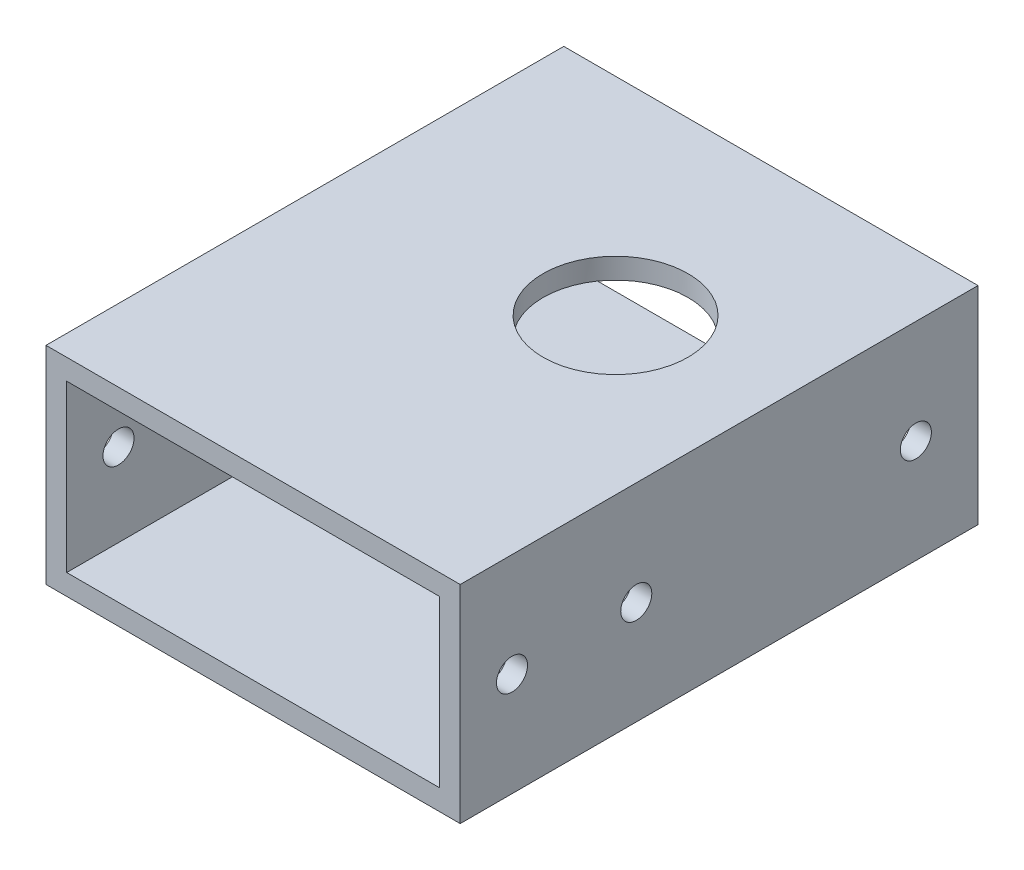
SolidWorks part; units mm, degrees
ref_plane "前视基准面" through (0, 0, 0) normal (0, 0, 1) x (1, 0, 0)
ref_plane "上视基准面" through (0, 0, 0) normal (0, 1, 0) x (1, 0, 0)
ref_plane "右视基准面" through (0, 0, 0) normal (1, 0, 0) x (0, 0, -1)
other "Configuration Table"
sketch "草图1" plane through (0, 0, 0) normal (0, 0, 1) x (1, 0, 0)
  line L1 (-20, 10) -> (20, 10)
  line L2 (-20, 10) -> (-20, -10)
  line L3 (-20, -10) -> (20, -10)
  line L4 (20, 10) -> (20, -10)
  line L5 (-20, 10) -> (20, -10) construction
  line L6 (-20, -10) -> (20, 10) construction
  line L7 (-18, 8) -> (18, 8)
  line L8 (-18, 8) -> (-18, -8)
  line L9 (-18, -8) -> (18, -8)
  line L10 (18, 8) -> (18, -8)
  line L11 (-18, 8) -> (18, -8) construction
  line L12 (-18, -8) -> (18, 8) construction
  point P0 (0, 0)
  point P6 (0, 0)
  dimension "D1" = 20
  dimension "D2" = 40
  dimension "D3" = 2
  dimension "D4" = 2
extrude "凸台-拉伸1" add sketch "草图1" along normal blind 50
sketch "草图2" plane through (0, 10, 0) normal (0, 1, 0) x (1, 0, 0)
  circle A0 centre (5, -20) radius 7
  dimension "D3" = 14
  dimension "D1" = 5
  dimension "D2" = 20
extrude "切除-拉伸1" cut sketch "草图2" against normal blind 20
sketch "草图3" plane through (20, 0, 0) normal (1, 0, 0) x (0, 0, -1)
  line L0 (-50, -10) -> (-50, 10) construction
  circle A0 centre (-6, 0) radius 1.5
  circle A1 centre (-33, 0) radius 1.5
  circle A2 centre (-45, 0) radius 1.5
  point P8 (0, 0)
  point P10 (-55.3623, 40.3551)
  dimension "D4" = 3
  dimension "D5" = 3
  dimension "D6" = 3
  dimension "D1" = 5
  dimension "D2" = 12
  dimension "D3" = 27
extrude "切除-拉伸2" cut sketch "草图3" against normal blind 50
